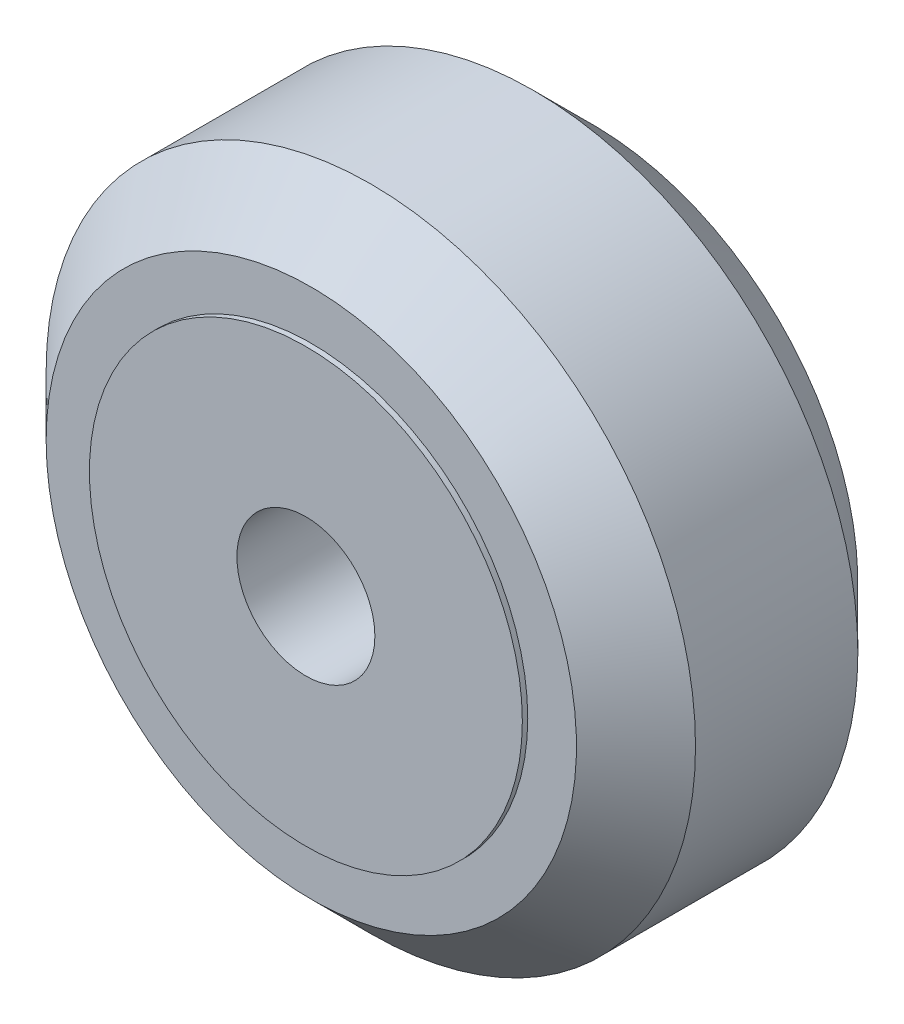
SolidWorks part; units mm, degrees
ref_plane "Front Plane" through (0, 0, 0) normal (0, 0, 1) x (1, 0, 0)
ref_plane "Top Plane" through (0, 0, 0) normal (0, 1, 0) x (1, 0, 0)
ref_plane "Right Plane" through (0, 0, 0) normal (1, 0, 0) x (0, 0, -1)
sketch "Sketch1" plane through (0, 0, 0) normal (1, 0, 0) x (0, 0, -1)
  line L0 (0, 0) -> (-14.1085, 0) construction
  line L1 (-0.6451, 8) -> (-11.0451, 8)
  line L2 (-11.0451, 8) -> (-11.0451, 9.8)
  line L3 (-11.0451, 9.8) -> (-8.8451, 12)
  line L4 (-8.8451, 12) -> (-2.8451, 12)
  line L5 (-2.8451, 12) -> (-0.6451, 9.8)
  line L6 (-0.6451, 9.8) -> (-0.6451, 8)
  point P5 (-5.8451, 12)
  point P10 (-5.8451, 8)
  dimension "D1" = 6
  dimension "D2" = 10.4
  dimension "D3" = 135
  dimension "D4" = 24
  dimension "D5" = 16
revolve "Revolve1" add sketch "Sketch1" angle 360 about L0
sketch "Sketch2" plane through (0, 0, 11.0451) normal (0, 0, 1) x (1, 0, 0)
  circle A0 centre (0, 0) radius 8
  circle A1 centre (0, 0) radius 2.55
  dimension "D1" = 5.1
  dimension "D2" = 16
extrude "Boss-Extrude1" add sketch "Sketch2" against normal blind 10.6
sketch "Sketch3" plane through (0, 0, 11.0451) normal (0, 0, 1) x (1, 0, 0)
  circle A0 centre (0, 0) radius 2.55
  circle A1 centre (0, 0) radius 8
  dimension "D1" = 5.1
  dimension "D2" = 16
extrude "Boss-Extrude2" add sketch "Sketch3" along normal blind 0.2
